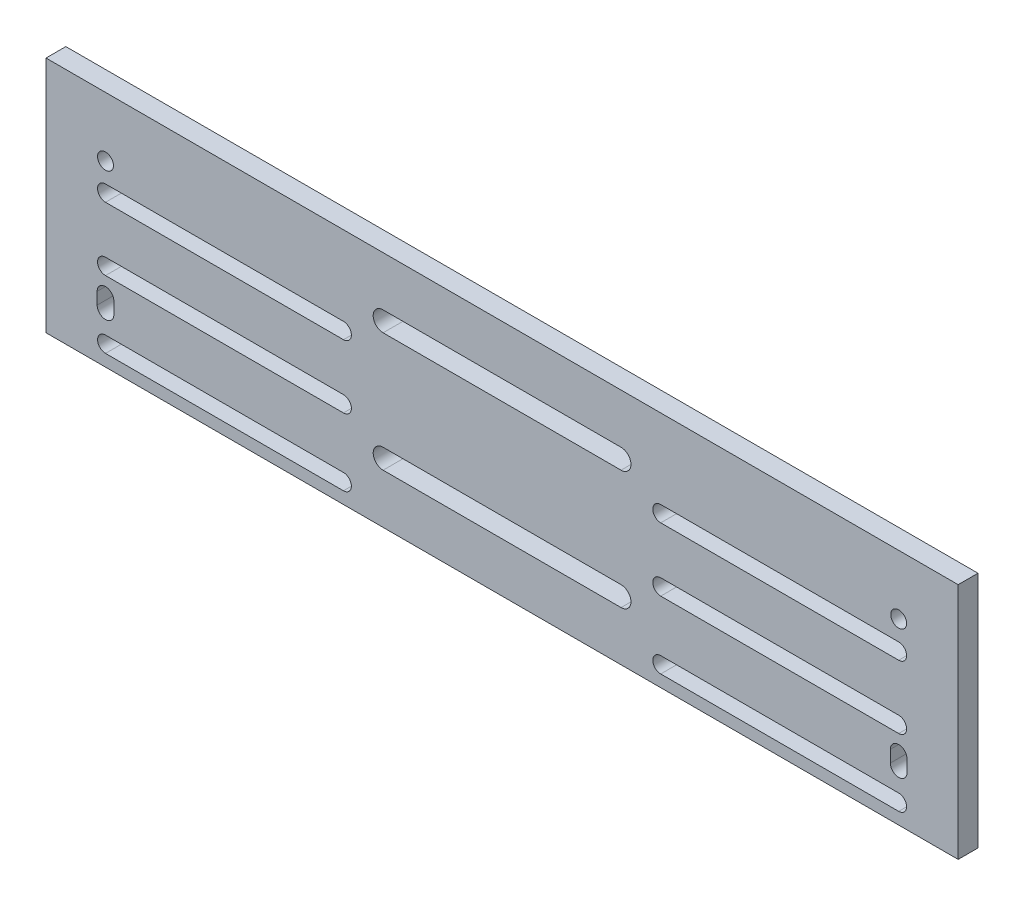
SolidWorks part; units mm, degrees
material "1060 合金"
ref_plane "前视基准面" through (0, 0, 0) normal (0, 0, 1) x (1, 0, 0)
ref_plane "上视基准面" through (0, 0, 0) normal (0, 1, 0) x (1, 0, 0)
ref_plane "右视基准面" through (0, 0, 0) normal (1, 0, 0) x (0, 0, -1)
sketch "草图2" plane through (0, 0, 0) normal (0, 0, 1) x (1, 0, 0)
  line L0 (-100, -17.5) -> (-100, -14.5) construction
  line L5 (-115, -30) -> (115, -30)
  line L6 (-115, -30) -> (-115, 30)
  line L7 (-115, 30) -> (115, 30)
  line L8 (115, -30) -> (115, 30)
  line L9 (-115, -30) -> (115, 30) construction
  line L10 (-115, 30) -> (115, -30) construction
  line L15 (-30, 15) -> (30, 15) construction
  line L16 (-30, 17.5) -> (30, 17.5)
  line L17 (0, -55) -> (0, 55) construction
  line L18 (40, -25) -> (100, -25) construction
  line L23 (40, -23) -> (100, -23)
  line L24 (40, -27) -> (100, -27)
  line L25 (-100, 8) -> (-40, 8) construction
  line L30 (-100, 10) -> (-40, 10)
  line L31 (-100, 6) -> (-40, 6)
  line L32 (55, 0) -> (-55, 0) construction
  line L33 (-100, -8) -> (-40, -8) construction
  line L34 (-100, -10) -> (-40, -10)
  line L35 (-100, -6) -> (-40, -6)
  line L36 (100, -8) -> (40, -8) construction
  line L37 (100, -10) -> (40, -10)
  line L38 (100, -6) -> (40, -6)
  line L39 (100, 8) -> (40, 8) construction
  line L40 (100, 10) -> (40, 10)
  line L41 (100, 6) -> (40, 6)
  line L42 (-102.1, -17.5) -> (-102.1, -14.5)
  line L43 (-97.9, -17.5) -> (-97.9, -14.5)
  line L44 (100, -17.5) -> (100, -14.5) construction
  line L45 (102.1, -17.5) -> (102.1, -14.5)
  line L46 (97.9, -17.5) -> (97.9, -14.5)
  line L47 (-30, 12.5) -> (30, 12.5)
  line L48 (-30, -15) -> (30, -15) construction
  line L49 (-30, -17.5) -> (30, -17.5)
  line L50 (-30, -12.5) -> (30, -12.5)
  line L51 (-40, -25) -> (-100, -25) construction
  line L52 (-40, -23) -> (-100, -23)
  line L53 (-40, -27) -> (-100, -27)
  circle A4 centre (-100, 15) radius 2
  circle A7 centre (100, 15) radius 2
  arc A8 (40, -23) -> (40, -27) centre (40, -25) ccw
  arc A9 (100, -27) -> (100, -23) centre (100, -25) ccw
  arc A14 (-100, 10) -> (-100, 6) centre (-100, 8) ccw
  arc A15 (-40, 6) -> (-40, 10) centre (-40, 8) ccw
  arc A16 (-100, -10) -> (-100, -6) centre (-100, -8) cw
  arc A17 (-40, -6) -> (-40, -10) centre (-40, -8) cw
  arc A18 (100, -10) -> (100, -6) centre (100, -8) ccw
  arc A19 (40, -6) -> (40, -10) centre (40, -8) ccw
  arc A20 (100, 10) -> (100, 6) centre (100, 8) cw
  arc A21 (40, 6) -> (40, 10) centre (40, 8) cw
  arc A22 (-102.1, -17.5) -> (-97.9, -17.5) centre (-100, -17.5) ccw
  arc A23 (-97.9, -14.5) -> (-102.1, -14.5) centre (-100, -14.5) ccw
  arc A24 (102.1, -17.5) -> (97.9, -17.5) centre (100, -17.5) cw
  arc A25 (97.9, -14.5) -> (102.1, -14.5) centre (100, -14.5) cw
  arc A26 (-30, 17.5) -> (-30, 12.5) centre (-30, 15) ccw
  arc A27 (30, 12.5) -> (30, 17.5) centre (30, 15) ccw
  arc A28 (-30, -17.5) -> (-30, -12.5) centre (-30, -15) cw
  arc A29 (30, -12.5) -> (30, -17.5) centre (30, -15) cw
  arc A30 (-40, -23) -> (-40, -27) centre (-40, -25) cw
  arc A31 (-100, -27) -> (-100, -23) centre (-100, -25) cw
  point P0 (0, 0)
  point P4 (0, 0)
  point P9 (0, 15)
  point P17 (-100, -16)
  point P26 (70, -25)
  point P28 (70, -25)
  point P33 (-70, 8)
  point P35 (-70, 8)
  point P45 (-70, -8)
  point P52 (70, -8)
  point P59 (70, 8)
  point P65 (-100, -16)
  point P70 (100, -16)
  point P76 (0, -15)
  point P83 (-70, -25)
  dimension "D5" = 15
  dimension "D11" = 4
  dimension "D12" = 2.1
  dimension "D15" = 2
  dimension "D18" = 70
  dimension "D20" = 2
  dimension "D3" = 2.5
  dimension "D1" = 230
  dimension "D2" = 60
  dimension "D4" = 60
  dimension "D9" = 15
  dimension "D10" = 45
  dimension "D13" = 15
  dimension "D14" = 3
  dimension "D16" = 60
  dimension "D17" = 5
  dimension "D19" = 8
  dimension "D21" = 60
  dimension "D22" = 31
other "对齐组1"
extrude "凸台-拉伸1" add sketch "草图2" along normal blind 5
